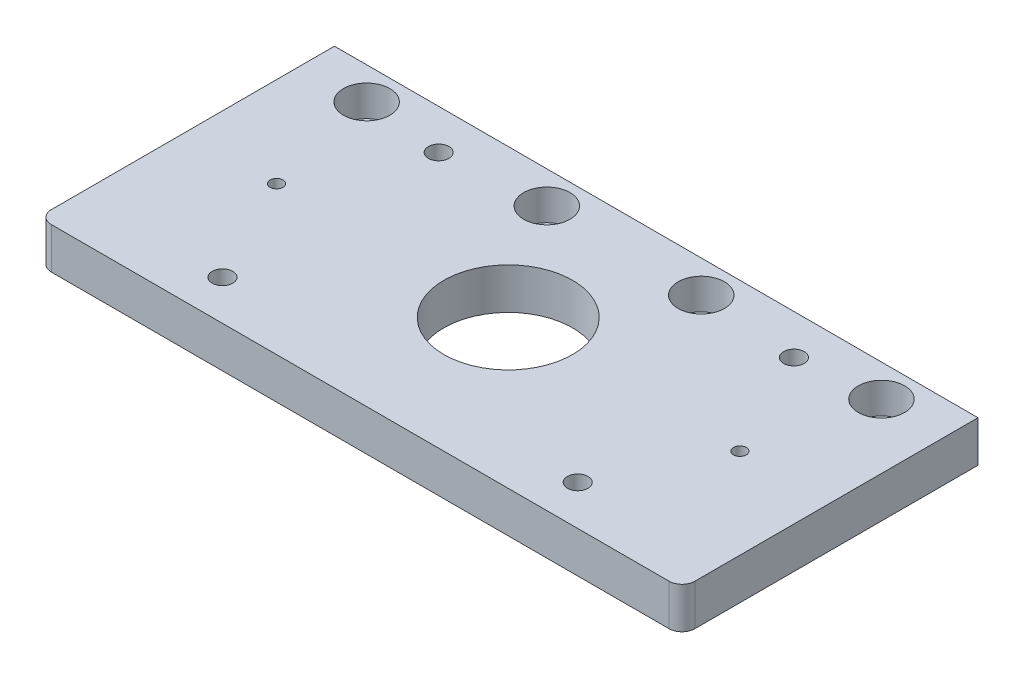
SolidWorks part; units mm, degrees
ref_plane "前视基准面" through (0, 0, 0) normal (0, 0, 1) x (1, 0, 0)
ref_plane "上视基准面" through (0, 0, 0) normal (0, 1, 0) x (1, 0, 0)
ref_plane "右视基准面" through (0, 0, 0) normal (1, 0, 0) x (0, 0, -1)
other "Configuration Table"
sketch "草图1" plane through (0, 0, 0) normal (0, 1, 0) x (1, 0, 0)
  line L1 (-125, 57.5) -> (125, 57.5)
  line L2 (-125, 57.5) -> (-125, -52.5)
  line L3 (-120, -57.5) -> (120, -57.5)
  line L4 (125, 57.5) -> (125, -52.5)
  circle A0 centre (0, 0) radius 25
  arc A1 (120, -57.5) -> (125, -52.5) centre (120, -52.5) ccw
  arc A2 (-125, -52.5) -> (-120, -57.5) centre (-120, -52.5) ccw
  circle A3 centre (69, -42) radius 4
  circle A4 centre (69, 42) radius 4
  circle A5 centre (-69, -42) radius 4
  circle A6 centre (-69, 42) radius 4
  circle A7 centre (30, 45) radius 6
  circle A8 centre (100, 45) radius 6
  circle A9 centre (-100, 45) radius 6
  circle A10 centre (-30, 45) radius 6
  dimension "D1" = 5
extrude "凸台-拉伸1" add sketch "草图1" along normal blind 16
sketch "草图2" plane through (0, 16, 0) normal (0, 1, 0) x (1, 0, 0)
  circle A0 centre (-100, 45) radius 9
  circle A1 centre (-30, 45) radius 9
  circle A2 centre (30, 45) radius 9
  circle A3 centre (100, 45) radius 9
extrude "切除-拉伸1" cut sketch "草图2" against normal blind 12
sketch "草图3" plane through (0, 16, 0) normal (0, 1, 0) x (1, 0, 0)
  circle A0 centre (-90, 0) radius 2.5
  circle A1 centre (90, 0) radius 2.5
extrude "切除-拉伸2" cut sketch "草图3" against normal blind 41
sketch "草图4" plane through (0, 0, 0) normal (0, -1, 0) x (1, 0, 0)
  circle A0 centre (-90, 0) radius 12.5
  circle A1 centre (90, 0) radius 12.5
extrude "切除-拉伸3" cut sketch "草图4" against normal blind 12
